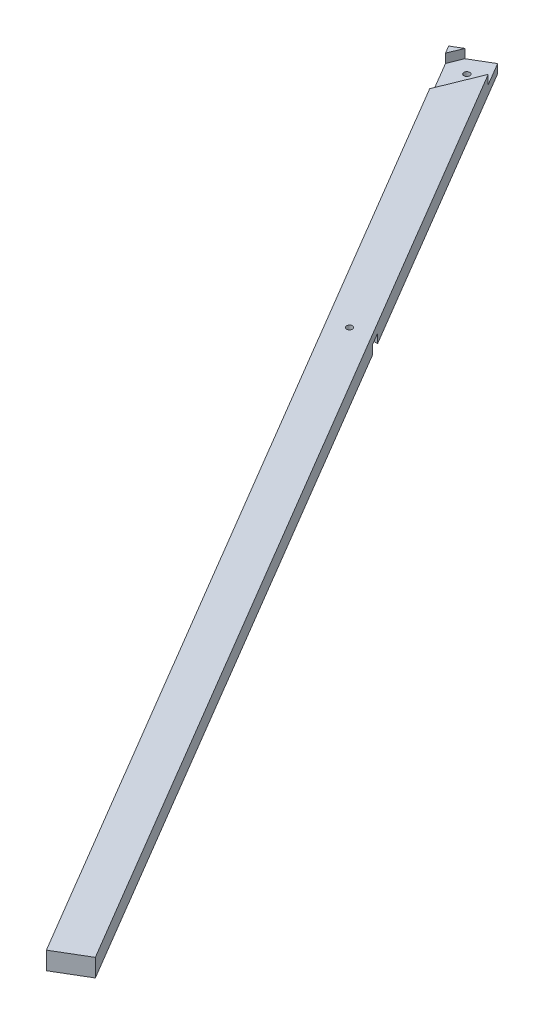
SolidWorks part; units mm, degrees
ref_plane "Front Plane" through (0, 0, 0) normal (0, 0, 1) x (1, 0, 0)
ref_plane "Top Plane" through (0, 0, 0) normal (0, 1, 0) x (1, 0, 0)
ref_plane "Right Plane" through (0, 0, 0) normal (1, 0, 0) x (0, 0, -1)
sketch "Sketch2" plane through (0, 0, 0) normal (0, 1, 0) x (1, 0, 0)
  line L0 (0, 0) -> (0, -38.1)
  line L1 (0, -38.1) -> (-1219.2, -38.1)
  line L2 (-1219.2, -38.1) -> (-1219.2, 0)
  line L3 (-1219.2, 0) -> (0, 0)
  line L4 (-323.85, -19.05) -> (-19.05, -19.05)
  line L5 (-19.05, -19.05) -> (-200.025, 287.0536)
  line L6 (-200.025, 287.0536) -> (-323.85, -19.05)
  line L7 (-323.85, -19.05) -> (-341.5098, -11.9062)
  line L8 (-323.85, -19.05) -> (-306.1902, -26.1937)
  line L9 (-341.5098, -11.9062) -> (-348.6536, -29.5661)
  line L10 (-306.1902, -26.1937) -> (-311.0065, -38.1)
  line L11 (-348.6536, -29.5661) -> (-313.3339, -43.8536)
  line L12 (108.5464, 1100.6626) -> (143.8661, 1086.3751)
  line L13 (143.8661, 1086.3751) -> (-295.5943, 0)
  line L14 (-341.5098, -11.9062) -> (108.5464, 1100.6626)
  line L15 (-200.025, 287.0536) -> (-183.6266, 296.7487)
  line L16 (-183.6266, 296.7487) -> (-193.3217, 313.1471)
  line L17 (-193.3217, 313.1471) -> (-226.1185, 293.7569)
  line L18 (-226.1185, 293.7569) -> (-52.4431, 0)
  line L19 (394.3672, -755.7411) -> (427.164, -736.3509)
  line L20 (427.164, -736.3509) -> (0, -13.8399)
  line L21 (-303.3004, -19.05) -> (-306.1902, -26.1937)
  line L22 (-8.1824, 0) -> (-183.6266, 296.7487)
  line L23 (-29.9176, -38.1) -> (394.3672, -755.7411)
  line L24 (-29.9176, -38.1) -> (-52.4431, 0)
  line L25 (0, -13.8399) -> (-8.1824, 0)
  line L26 (-303.3004, -19.05) -> (-295.5943, 0)
  line L27 (-313.3339, -43.8536) -> (-311.0065, -38.1)
  circle A0 centre (-19.05, -19.05) radius 3.175
  circle A1 centre (-323.85, -19.05) radius 3.175
  circle A2 centre (-200.025, 287.0536) radius 3.175
  point P22 (0, 730.7286)
  dimension "D5" = 6.35
  dimension "D6" = 6.35
  dimension "D18" = 6.35
  dimension "D1" = 38.1
  dimension "D2" = 1219.2
  dimension "D3" = 19.05
  dimension "D4" = 19.05
  dimension "D7" = 304.8
  dimension "D8" = 19.05
  dimension "D9" = 330.2
  dimension "D10" = 355.6
  dimension "D11" = 90
  dimension "D12" = 19.05
  dimension "D13" = 90
  dimension "D14" = 19.05
  dimension "D15" = 19.05
  dimension "D16" = 19.05
  dimension "D19" = 90
  dimension "D20" = 19.05
  dimension "D21" = 19.05
  dimension "D22" = 38.1
  dimension "D23" = 1219.2
  dimension "D24" = 38.1
  dimension "D25" = 67.976
  dimension "D26" = 295.5943
  dimension "D27" = 311.0065
  dimension "D28" = 8.1824
  dimension "D29" = 29.9176
  dimension "D30" = 52.4431
  dimension "D17" = 1219.2
extrude "Boss-Extrude4" add sketch "Sketch2" along normal blind 19.05 contours L16 L17 L18 L24 L23 L19 L20 L25 L22
sketch "Sketch8" plane through (0, 19.05, 0) normal (0, 1, 0) x (1, 0, 0)
  line L0 (-215.268, 300.172) -> (-221.2168, 285.4661)
  line L1 (-341.5098, -11.9062) -> (108.5464, 1100.6626) construction
  line L2 (-193.3217, 313.1471) -> (-226.1185, 293.7569) construction
  line L3 (-226.1185, 293.7569) -> (-52.4431, 0) construction
  line L4 (-221.2168, 285.4661) -> (-196.8141, 244.1911)
  line L5 (143.8661, 1086.3751) -> (-295.5943, 0) construction
  line L6 (-196.8141, 244.1911) -> (-178.8332, 288.6411)
  line L7 (-8.1824, 0) -> (-183.6266, 296.7487) construction
  line L8 (-178.8332, 288.6411) -> (-193.3217, 313.1471)
  line L9 (-193.3217, 313.1471) -> (-215.268, 300.172)
  line L10 (-8.1824, 0) -> (0, -13.8399)
  line L11 (0, -13.8399) -> (0, -38.1)
  line L12 (0, -38.1) -> (-29.9176, -38.1)
  line L13 (-29.9176, -38.1) -> (-52.4431, 0)
  line L14 (-52.4431, 0) -> (-8.1824, 0)
  line M1 (427.164, -736.3509) -> (-193.3217, 313.1471)
  line M2 (-193.3217, 313.1471) -> (-226.1185, 293.7569)
  line M3 (-226.1185, 293.7569) -> (394.3672, -755.7411)
extrude "Cut-Extrude5" cut sketch "Sketch8" against normal blind 9.525 contours L6 L0 M3 M1 M2
sketch "Sketch9" plane through (0, 0, 0) normal (0, -1, 0) x (1, 0, 0)
  line L0 (-52.4431, 0) -> (-29.9176, 38.1)
  line L1 (-29.9176, 38.1) -> (0, 38.1)
  line L2 (0, 38.1) -> (0, 13.8399)
  line L3 (0, 13.8399) -> (-8.1824, 0)
  line L4 (-8.1824, 0) -> (-52.4431, 0)
extrude "Cut-Extrude6" cut sketch "Sketch9" against normal blind 9.525
sketch "Sketch10" plane through (0, 0, 0) normal (0, -1, 0) x (1, 0, 0)
  circle A0 centre (-200.025, -287.0536) radius 3.175
  circle A1 centre (-19.05, 19.05) radius 3.175
extrude "Cut-Extrude7" cut sketch "Sketch10" against normal blind 19.05
